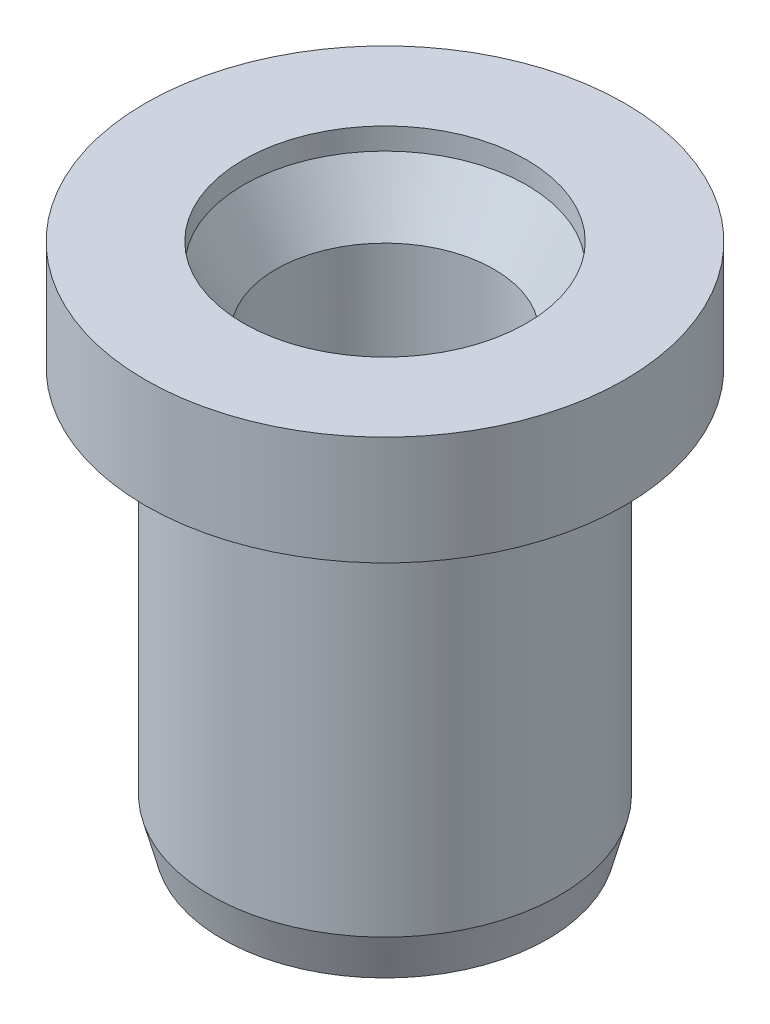
SolidWorks part; units mm, degrees
material "K110"
ref_plane "Front Plane" through (0, 0, 0) normal (0, 0, 1) x (1, 0, 0)
ref_plane "Top Plane" through (0, 0, 0) normal (0, 1, 0) x (1, 0, 0)
ref_plane "Right Plane" through (0, 0, 0) normal (1, 0, 0) x (0, 0, -1)
sketch "Sketch1" plane through (0, 0, 0) normal (0, 0, 1) x (1, 0, 0)
  line L0 (0, 0) -> (4, 0)
  line L1 (4, 0) -> (4, 9.3)
  line L2 (4, 9.3) -> (3.8, 9.3)
  line L3 (3.8, 9.3) -> (3.8, 9.5)
  line L4 (3.8, 9.5) -> (5.5, 9.5)
  line L5 (5.5, 9.5) -> (5.5, 12)
  line L6 (5.5, 12) -> (0, 12)
  line L7 (0, 12) -> (0, 0)
  line L8 (0, -5) -> (0, 17) construction
  dimension "D1" = 0.2
  dimension "D2" = 5
  dimension "D3" = 5
  dimension "D4" = 0.2
  dimension "L1" = 12
  dimension "L2" = 9.5
  dimension "Dia3" = 11
  dimension "Dia" = 8
revolve "Revolve1" add sketch "Sketch1" angle 360 about L8
sketch "Sketch2" plane through (0, 12, 0) normal (0, 1, 0) x (1, 0, 0)
  circle A0 centre (0, 0) radius 2.5
  dimension "Dia1" = 5
extrude "Cut-Extrude1" cut sketch "Sketch2" against normal through all
chamfer "Chamfer1" distance 1 angle 15 1 edges at (0, 0, -4)
sketch "Sketch3" plane through (0, 0, 0) normal (0, 0, 1) x (1, 0, 0)
  line L0 (0, -5) -> (0, 17) construction
  line L1 (5.5, 12) -> (-5.5, 12) construction
  line L2 (0, 12) -> (3.25, 12)
  line L3 (2.5, 12) -> (-2.5, 12) construction
  line L4 (3.25, 12) -> (3.25, 11.5)
  line L5 (3.25, 11.5) -> (2.5, 10.201)
  line L6 (2.5, 0) -> (2.5, 12) construction
  line L7 (2.5, 10.201) -> (0, 10.201)
  line L8 (0, 10.201) -> (0, 12)
  dimension "D1" = 5
  dimension "D2" = 5
  dimension "Parallel Dia" = 6.5
  dimension "K" = 0.5
  dimension "D5" = 30
revolve "Cut-Revolve1" cut sketch "Sketch3" angle 360 about L0
